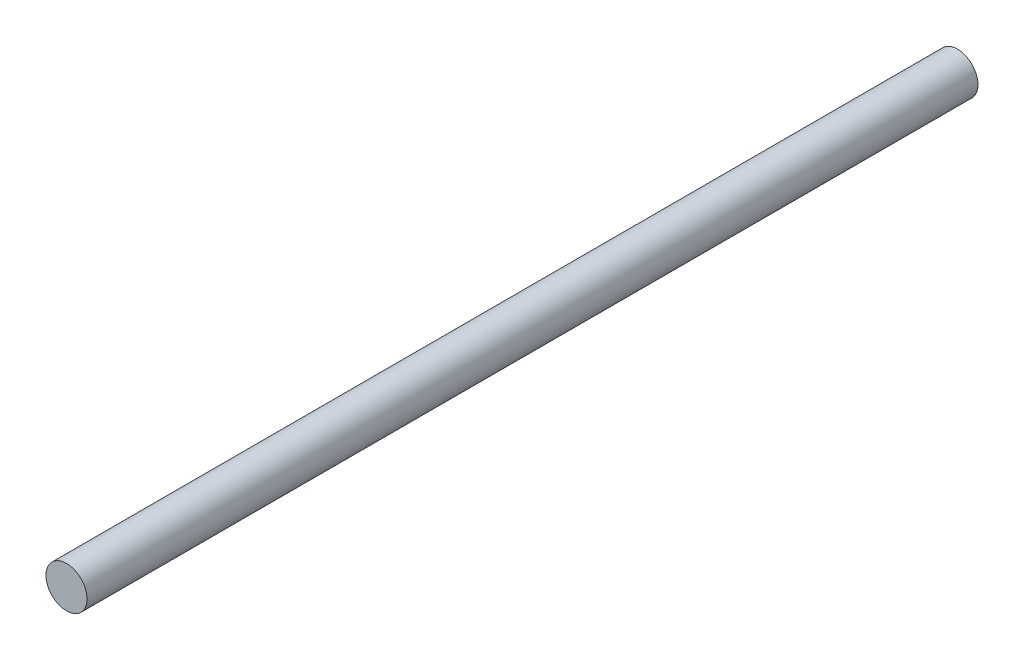
SolidWorks part; units mm, degrees
ref_plane "前视基准面" through (0, 0, 0) normal (0, 0, 1) x (1, 0, 0)
ref_plane "上视基准面" through (0, 0, 0) normal (0, 1, 0) x (1, 0, 0)
ref_plane "右视基准面" through (0, 0, 0) normal (1, 0, 0) x (0, 0, -1)
sketch "草图1" plane through (0, 0, 0) normal (0, 0, 1) x (1, 0, 0)
  circle A0 centre (0, 0) radius 1.5
  dimension "D1" = 3
extrude "凸台-拉伸1" add sketch "草图1" along normal blind 65
